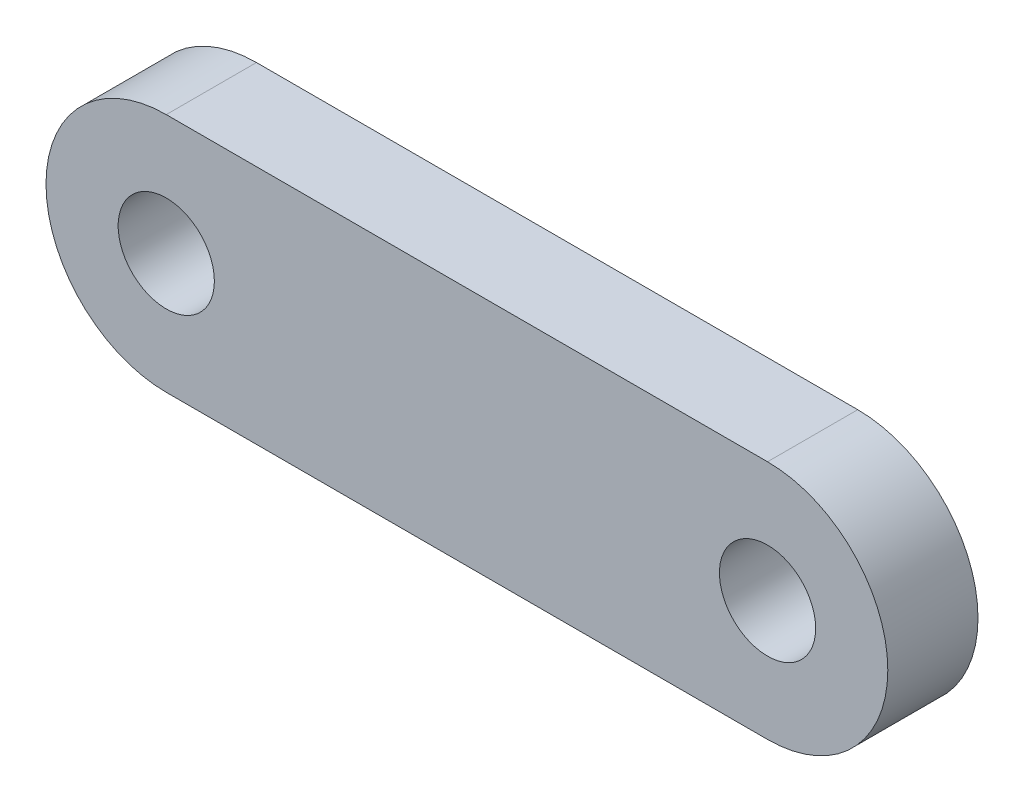
SolidWorks part; units mm, degrees
ref_plane "Front Plane" through (0, 0, 0) normal (0, 0, 1) x (1, 0, 0)
ref_plane "Top Plane" through (0, 0, 0) normal (0, 1, 0) x (1, 0, 0)
ref_plane "Right Plane" through (0, 0, 0) normal (1, 0, 0) x (0, 0, -1)
sketch "Sketch1" plane through (0, 0, 0) normal (0, 0, 1) x (1, 0, 0)
  line L0 (-10, 0) -> (10, 0) construction
  line L1 (-10, 4) -> (10, 4)
  line L2 (-10, -4) -> (10, -4)
  arc A0 (-10, 4) -> (-10, -4) centre (-10, 0) ccw
  arc A1 (10, -4) -> (10, 4) centre (10, 0) ccw
  circle A3 centre (-10, 0) radius 1.6
  circle A4 centre (10, 0) radius 1.6
  point P3 (0, 0)
  dimension "D3" = 3.2
  dimension "D1" = 20
  dimension "D2" = 8
extrude "Boss-Extrude1" add sketch "Sketch1" along normal blind 3
